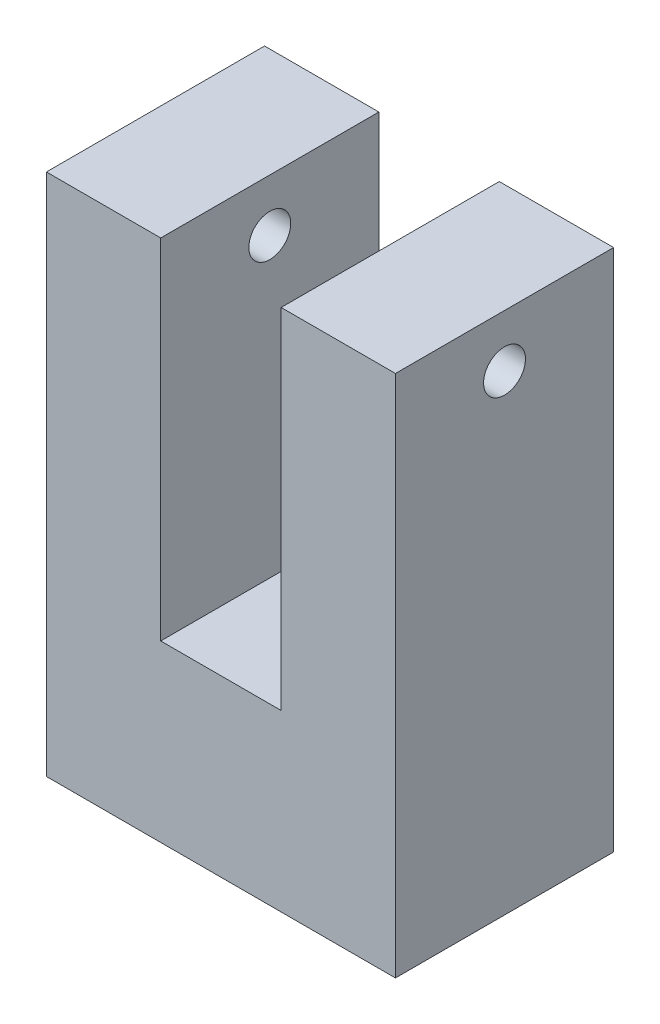
SolidWorks part; units mm, degrees
material "6061-T6 (SS)"
ref_plane "Front Plane" through (0, 0, 0) normal (0, 0, 1) x (1, 0, 0)
ref_plane "Top Plane" through (0, 0, 0) normal (0, 1, 0) x (1, 0, 0)
ref_plane "Right Plane" through (0, 0, 0) normal (1, 0, 0) x (0, 0, -1)
sketch "Sketch1" plane through (0, 0, 0) normal (0, 1, 0) x (1, 0, 0)
  line L1 (-12.7, -7.9375) -> (12.7, -7.9375)
  line L2 (-12.7, -7.9375) -> (-12.7, 7.9375)
  line L3 (-12.7, 7.9375) -> (12.7, 7.9375)
  line L4 (12.7, -7.9375) -> (12.7, 7.9375)
  line L5 (-12.7, -7.9375) -> (12.7, 7.9375) construction
  line L6 (-12.7, 7.9375) -> (12.7, -7.9375) construction
  point P0 (0, 0)
  dimension "D1" = 15.875
  dimension "D2" = 25.4
extrude "Boss-Extrude1" add sketch "Sketch1" along normal blind 38.1
sketch "Sketch2" plane through (0, 0, 7.9375) normal (0, 0, 1) x (1, 0, 0)
  line L0 (0, 38.1) -> (0, 0) construction
  line L1 (-12.7, 38.1) -> (12.7, 38.1) construction
  line L2 (-12.7, 0) -> (12.7, 0) construction
  line L4 (-4.3815, 12.7) -> (4.3815, 12.7)
  line L5 (-4.3815, 12.7) -> (-4.3815, 38.1)
  line L6 (-4.3815, 38.1) -> (4.3815, 38.1)
  line L7 (4.3815, 12.7) -> (4.3815, 38.1)
  line L8 (-4.3815, 12.7) -> (4.3815, 38.1) construction
  line L9 (-4.3815, 38.1) -> (4.3815, 12.7) construction
  point P6 (0, 25.4)
  dimension "D1" = 8.763
  dimension "D2" = 25.4
extrude "Cut-Extrude1" cut sketch "Sketch2" against normal through all
sketch "Sketch3" plane through (12.7, 0, 0) normal (1, 0, 0) x (0, 0, -1)
  line L0 (0, 38.1) -> (0, 0) construction
  line L1 (-7.9375, 38.1) -> (7.9375, 38.1) construction
  line L2 (-7.9375, 0) -> (7.9375, 0) construction
  circle A0 centre (0, 34.29) radius 1.524
  dimension "D1" = 34.29
  dimension "D2" = 3.048
extrude "Cut-Extrude2" cut sketch "Sketch3" against normal through all
sketch "Sketch4" plane through (0, 0, 0) normal (0, -1, 0) x (1, 0, 0)
  circle A0 centre (0, 0) radius 2.0955
  dimension "D1" = 4.191
extrude "Cut-Extrude3" cut sketch "Sketch4" against normal through all
